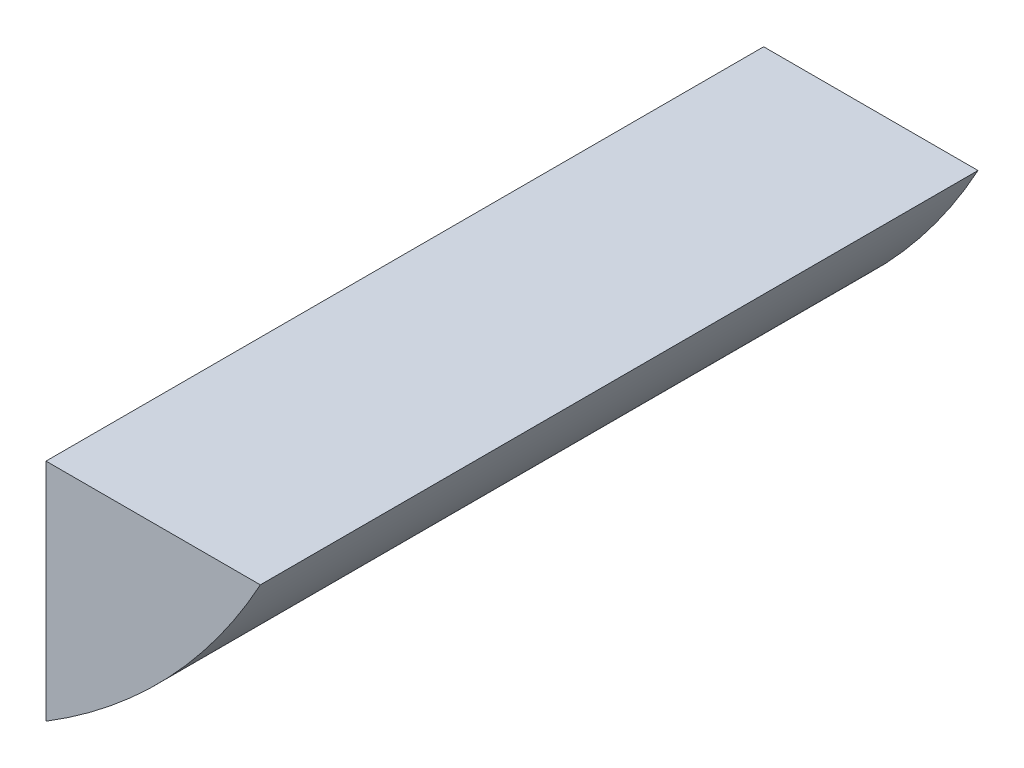
SolidWorks part; units mm, degrees
material "ABS"
ref_plane "Płaszczyzna przednia" through (0, 0, 0) normal (0, 0, 1) x (1, 0, 0)
ref_plane "Płaszczyzna górna" through (0, 0, 0) normal (0, 1, 0) x (1, 0, 0)
ref_plane "Płaszczyzna prawa" through (0, 0, 0) normal (1, 0, 0) x (0, 0, -1)
sketch "Szkic1" plane through (0, 0, 0) normal (0, 0, 1) x (1, 0, 0)
  line L7 (15.9573, -36.0859) -> (18.0264, -34.8795)
  line L13 (18.0264, -54.1634) -> (18.0264, -20.1634) construction
  line L14 (32.9596, -19.1815) -> (18.0264, -19.1815)
  line L15 (18.0264, -19.1815) -> (18.0264, -34.8795)
  arc A7 (18.0264, -34.8795) -> (32.9596, -19.1815) centre (-3.9829, 1.0093) ccw
  point P0 (19.0954, -25.0519)
extrude "Dodanie-wyciągnięcie1" add sketch "Szkic1" along normal blind 50 contours L7 A7 L14 L15
